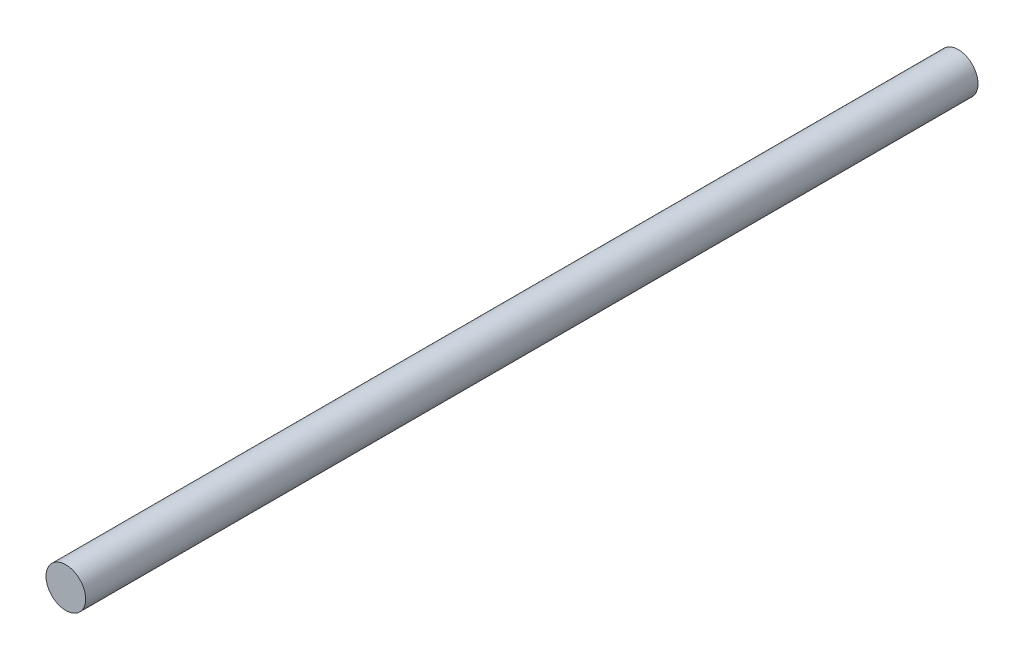
SolidWorks part; units mm, degrees
ref_plane "Front" through (0, 0, 0) normal (0, 0, 1) x (1, 0, 0)
ref_plane "Top" through (0, 0, 0) normal (0, 1, 0) x (1, 0, 0)
ref_plane "Right" through (0, 0, 0) normal (1, 0, 0) x (0, 0, -1)
sketch "Sketch1" plane through (0, 0, 0) normal (0, 0, 1) x (1, 0, 0)
  circle A0 centre (0, 0) radius 4
  dimension "D1" = 8
extrude "Boss-Extrude1" add sketch "Sketch1" along normal blind 180
equation "\"linear-bar-dia\"= 8mm ' Diameter of the metal slide bar used on the X Axis"
equation "\"material-thickness\"= 12.4mm"
equation "\"yplate-height\"= 200mm"
equation "\"D1@Boss-Extrude1\"= \"yplate-height\" - 20"
equation "\"D1@Sketch1\"=\"linear-bar-dia\""
